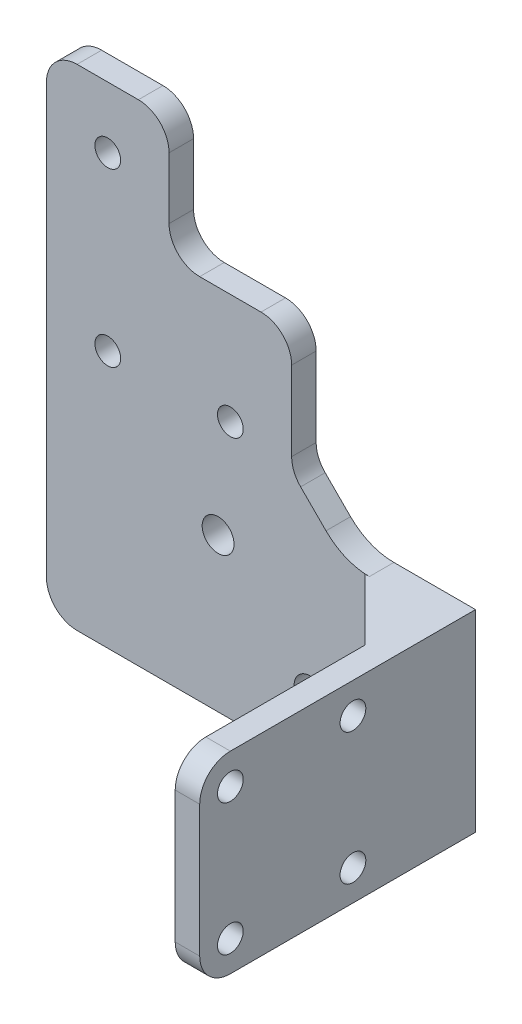
SolidWorks part; units mm, degrees
ref_plane "Спереди" through (0, 0, 0) normal (0, 0, 1) x (1, 0, 0)
ref_plane "Сверху" through (0, 0, 0) normal (0, 1, 0) x (1, 0, 0)
ref_plane "Справа" through (0, 0, 0) normal (1, 0, 0) x (0, 0, -1)
sketch "Model" plane through (0, 0, 0) normal (0, 0, 1) x (1, 0, 0)
  line L92 (308.3927, 233.3937) -> (308.3927, 210.4648)
  line L93 (303.3927, 205.4648) -> (263.3927, 205.4648)
  line L94 (258.3928, 210.4648) -> (258.3928, 280.4647)
  line L95 (263.3927, 285.4647) -> (273.3927, 285.4647)
  line L96 (278.3927, 280.4647) -> (278.3927, 270.4647)
  line L97 (283.3927, 265.4647) -> (293.3927, 265.4647)
  line L98 (298.3927, 260.4647) -> (298.3927, 247.5358)
  line L99 (299.8571, 244.0003) -> (306.9282, 236.9292)
  circle A59 centre (286.3927, 230.4648) radius 2.6
  circle A60 centre (301.3927, 215.4648) radius 2.6
  circle A61 centre (268.3927, 275.4647) radius 2.1
  circle A62 centre (268.3927, 247.4648) radius 2.1
  circle A63 centre (288.3927, 247.4648) radius 2.1
  arc A173 (303.3927, 205.4648) -> (308.3927, 210.4648) centre (303.3927, 210.4648) ccw
  arc A174 (258.3928, 210.4648) -> (263.3927, 205.4648) centre (263.3927, 210.4648) ccw
  arc A175 (263.3927, 285.4647) -> (258.3928, 280.4647) centre (263.3927, 280.4647) ccw
  arc A176 (278.3927, 280.4647) -> (273.3927, 285.4647) centre (273.3927, 280.4647) ccw
  arc A177 (278.3927, 270.4647) -> (283.3927, 265.4647) centre (283.3927, 270.4647) ccw
  arc A178 (298.3927, 260.4647) -> (293.3927, 265.4647) centre (293.3927, 260.4647) ccw
  arc A179 (298.3927, 247.5358) -> (299.8571, 244.0003) centre (303.3927, 247.5358) ccw
  arc A180 (308.3927, 233.3937) -> (306.9282, 236.9292) centre (303.3927, 233.3937) ccw
extrude "Бобышка-Вытянуть1" add sketch "Model" along normal blind 4
sketch "Эскиз1" plane through (0, 0, 0) normal (0, 0, -1) x (-1, 0, 0)
  line L0 (-303.3927, 205.4648) -> (-308.3927, 205.4648) construction
  line L1 (-308.3927, 205.4648) -> (-308.3927, 210.4648) construction
  line L2 (-308.3927, 233.3937) -> (-308.3927, 236.9292) construction
  line L3 (-308.3927, 236.9292) -> (-306.9282, 236.9292) construction
  line L4 (-308.3927, 232.6159) -> (-308.3927, 210.4648)
  line L5 (-308.3927, 236.9292) -> (-320.3927, 236.9292)
  line L6 (-308.3927, 233.3937) -> (-308.3927, 232.6159)
  line L7 (-308.3927, 205.4648) -> (-320.3927, 205.4648)
  line L8 (-320.3927, 236.9292) -> (-320.3927, 205.4648)
  line L9 (-308.3927, 236.9292) -> (-303.3927, 236.9292)
  line L10 (-308.3927, 233.3937) -> (-308.3927, 232.6159)
  line L11 (-308.3927, 232.6159) -> (-303.3927, 232.6159)
  line L12 (-303.3927, 236.9292) -> (-303.3927, 232.6159)
  line L13 (-308.3927, 205.4648) -> (-300.2108, 205.4648)
  line L15 (-308.3927, 210.4648) -> (-300.2108, 210.4648)
  line L16 (-300.2108, 205.4648) -> (-300.2108, 210.4648)
  arc M10 (-308.3927, 210.4648) -> (-303.3927, 205.4648) centre (-303.3927, 210.4648) ccw
  arc M24 (-306.9282, 236.9292) -> (-308.3927, 233.3937) centre (-303.3927, 233.3937) ccw
  line M25 (-308.3927, 233.3937) -> (-308.3927, 210.4648)
  dimension "D1" = 12
extrude "Бобышка-Вытянуть2" add sketch "Эскиз1" against normal blind 4 contours L7 L13 L9 L5 L8 M10 M25 M24
fillet "Скругление1" radius 10 1 edges at (306.9282, 236.9292, 2)
sketch "Эскиз4" plane through (320.3927, 0, 0) normal (1, 0, 0) x (0, 0, -1)
  line L5 (0, 236.9292) -> (-40, 236.9292)
  line L6 (0, 236.9292) -> (0, 205.4648)
  line L8 (0, 205.4648) -> (-40, 205.4648)
  line L9 (-45, 231.9292) -> (-45, 210.4648)
  arc A6 (-45, 210.4648) -> (-40, 205.4648) centre (-40, 210.4648) ccw
  arc A7 (-45, 231.9292) -> (-40, 236.9292) centre (-40, 231.9292) cw
  circle A8 centre (-40, 231.9292) radius 2.1
  circle A9 centre (-40, 210.4648) radius 2.1
  circle A10 centre (-20, 231.9292) radius 2.1
  circle A11 centre (-20, 210.4648) radius 2.1
  point P27 (-45, 236.9292)
  dimension "D6" = 5
  dimension "D7" = 4.2
  dimension "D8" = 4.2
  dimension "D5" = 45
extrude "Бобышка-Вытянуть3" add sketch "Эскиз4" along normal blind 4
sketch "Эскиз5" plane through (0, 236.9292, 0) normal (0, 1, 0) x (1, 0, 0)
  line L5 (320.3927, -4) -> (310.3927, -4)
  line L6 (320.3927, -4) -> (311.0703, -4) construction
  line L7 (310.3927, -4) -> (320.3927, -14)
  line L8 (320.3927, -4) -> (320.3927, -40) construction
  line L9 (320.3927, -14) -> (320.3927, -4)
  dimension "D1" = 10
  dimension "D4" = 10
extrude "Бобышка-Вытянуть4" add sketch "Эскиз5" against normal blind 4
ref_plane "Плоскость1" through (0, 221.197, 0) normal (0, 1, 0) x (1, 0, 0)
mirror "Зеркальное отражение1" about plane through (0, 221.197, 0) normal (0, 1, 0) of "Бобышка-Вытянуть4"
